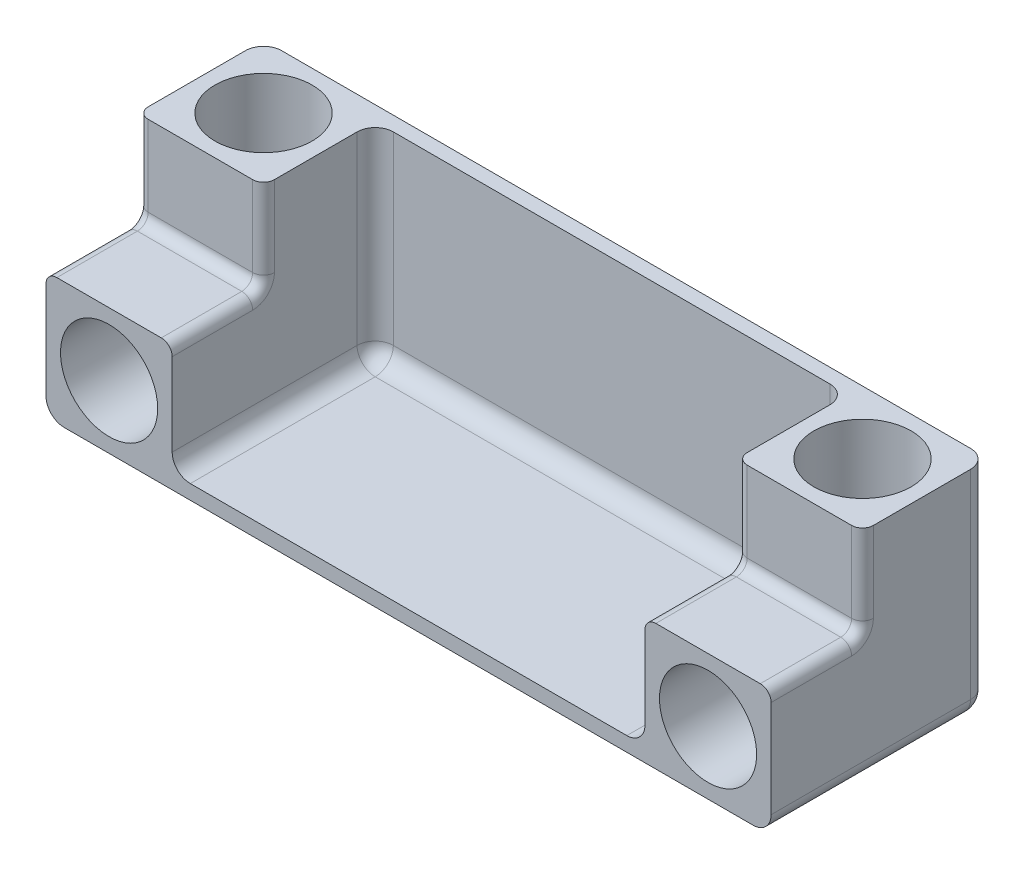
SolidWorks part; units mm, degrees
ref_plane "Front Plane" through (0, 0, 0) normal (0, 0, 1) x (1, 0, 0)
ref_plane "Top Plane" through (0, 0, 0) normal (0, 1, 0) x (1, 0, 0)
ref_plane "Right Plane" through (0, 0, 0) normal (1, 0, 0) x (0, 0, -1)
sketch "Sketch1" plane through (0, 0, 0) normal (0, 1, 0) x (1, 0, 0)
  line L0 (-65.2, 44.6799) -> (-65.2, -11.3201)
  line L1 (0, -11.3201) -> (-100, -11.3201)
  line L2 (0, -11.3201) -> (0, 48.6799)
  line L3 (0, 48.6799) -> (-100, 48.6799)
  line L4 (-100, -11.3201) -> (-100, 48.6799)
  line L5 (-65.2, 44.6799) -> (0, 44.6799)
  circle A0 centre (-82.6, 31.2799) radius 13.4
  dimension "D3" = 17.4
  dimension "D4" = 17.4
  dimension "D5" = 26.8
  dimension "D1" = 100
  dimension "D2" = 60
  dimension "D6" = 34.8
  dimension "D7" = 4
extrude "Boss-Extrude1" add sketch "Sketch1" along normal blind 56 contours L0 L5 L2 L3 L4 L1 A0
sketch "Sketch2" plane through (0, 0, 0) normal (0, 1, 0) x (1, 0, 0)
  line L1 (0, 48.6799) -> (-100, 48.6799)
  line L2 (0, 48.6799) -> (0, -11.3201)
  line L3 (0, -11.3201) -> (-100, -11.3201)
  line L4 (-100, 48.6799) -> (-100, -11.3201)
extrude "Boss-Extrude2" add sketch "Sketch2" against normal blind 4
sketch "Sketch3" plane through (0, 0, 11.3201) normal (0, 0, 1) x (1, 0, 0)
  line L0 (-100, 56) -> (-100, -4) construction
  line L2 (-100, -4) -> (0, -4) construction
  circle A0 centre (-82.6, 13.4) radius 13.4
  dimension "D2" = 17.4
  dimension "D3" = 26.8
  dimension "D1" = 17.4
extrude "Cut-Extrude1" cut sketch "Sketch3" against normal blind 25.2 contours A0
sketch "Sketch4" plane through (-100, 0, 0) normal (-1, 0, 0) x (0, 0, 1)
  line L0 (-48.6799, -4) -> (11.3201, -4) construction
  line L9 (11.3201, 56) -> (-13.8799, 56)
  line L10 (11.3201, 56) -> (11.3201, 30.8)
  line L11 (11.3201, 30.8) -> (-13.8799, 30.8)
  line L12 (-13.8799, 56) -> (-13.8799, 30.8)
  line L13 (-48.6799, 56) -> (-48.6799, -4) construction
  dimension "D1" = 34.8
  dimension "D3" = 34.8
extrude "Cut-Extrude2" cut sketch "Sketch4" against normal blind 51.2
sketch3d "3DSketch1"
  line L0 (0, 56, -44.6799) -> (0, 0, -44.6799) construction
  line L1 (0, 0, -44.6799) -> (0, 0, 11.3201) construction
ref_plane "Plane1" through (0, 0, 0) normal (-1, 0, 0) x (0, 0, 1)
mirror "Mirror2" about plane through (0, 0, 0) normal (-1, 0, 0) of "Cut-Extrude1", "Boss-Extrude2", "Boss-Extrude1", "Cut-Extrude2"
fillet "Fillet1" radius 5 5 edges at (0, 0, -44.6799) (-65.2, 0, -16.6799) (-65.2, 28, -44.6799) (65.2, 0, -16.6799) (65.2, 28, -44.6799)
fillet "Fillet2" radius 5 5 edges at (-100, -4, -18.6799) (-100, 26, -48.6799) (100, -4, -18.6799) (0, -4, -48.6799) (100, 26, -48.6799)
fillet "Fillet4" radius 3 5 edges at (-65.2, 30.8, -1.2799) (-100, 30.8, -1.2799) (-82.6, 30.8, -13.8799) (-100, 43.4, -13.8799) (-65.2, 43.4, -13.8799)
fillet "Fillet5" radius 3 5 edges at (100, 30.8, -1.2799) (65.2, 30.8, -1.2799) (100, 43.4, -13.8799) (65.2, 43.4, -13.8799) (82.6, 30.8, -13.8799)
